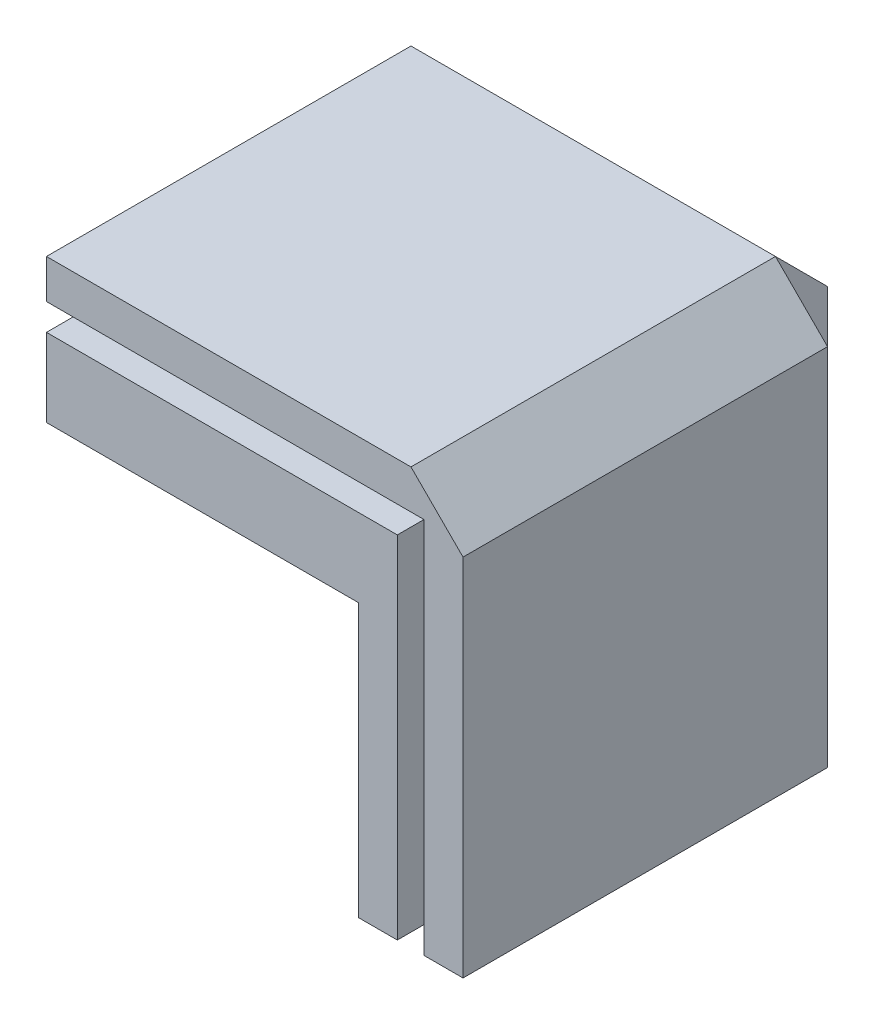
SolidWorks part; units mm, degrees
material "6061-T6 (SS)"
ref_plane "Front Plane" through (0, 0, 0) normal (0, 0, 1) x (1, 0, 0)
ref_plane "Top Plane" through (0, 0, 0) normal (0, 1, 0) x (1, 0, 0)
ref_plane "Right Plane" through (0, 0, 0) normal (1, 0, 0) x (0, 0, -1)
sketch "Sketch4" plane through (0, 0, 0) normal (0, 1, 0) x (1, 0, 0)
  line L1 (0, 0) -> (50.8, 0)
  line L2 (0, 0) -> (0, 50.8)
  line L3 (0, 50.8) -> (50.8, 50.8)
  line L4 (50.8, 0) -> (50.8, 50.8)
  dimension "D1" = 50.8
  dimension "D2" = 50.8
extrude "Boss-Extrude4" add sketch "Sketch4" along normal blind 50.8
sketch "Sketch5" plane through (0, 0, 0) normal (0, -1, 0) x (1, 0, 0)
  line L1 (0, 0) -> (38.0238, 0)
  line L2 (0, 0) -> (0, -38.0238)
  line L3 (0, -38.0238) -> (38.0238, -38.0238)
  line L4 (38.0238, 0) -> (38.0238, -38.0238)
  dimension "D1" = 38.0238
extrude "Cut-Extrude1" cut sketch "Sketch5" against normal blind 38.0238
sketch "Sketch6" plane through (0, 0, 0) normal (-1, 0, 0) x (0, 0, 1)
  line L7 (0, 50.8) -> (0, 38.0238) construction
  line L8 (-50.8, 0) -> (-38.0238, 0) construction
  line L9 (-46.0375, 0) -> (-42.7863, 0)
  line L10 (0, 46.0375) -> (0, 42.7863)
  line L13 (-46.0375, 4.7625) -> (-42.7863, 4.7625)
  line L14 (-42.7863, 4.7625) -> (-42.7863, 42.7863)
  line L15 (-42.7863, 42.7863) -> (-4.7625, 42.7863)
  line L16 (-4.7625, 42.7863) -> (-4.7625, 46.0375)
  line L17 (-4.7625, 46.0375) -> (-46.0375, 46.0375)
  line L18 (-46.0375, 46.0375) -> (-46.0375, 4.7625)
  line L20 (-42.7863, 0) -> (-42.7863, 42.7863)
  line L21 (-42.7863, 42.7863) -> (0, 42.7863)
  line L23 (0, 46.0375) -> (-46.0375, 46.0375)
  line L24 (-46.0375, 46.0375) -> (-46.0375, 0)
  dimension "D1" = 4.7625
extrude "Cut-Extrude2" cut sketch "Sketch6" against normal blind 31.6738
sketch "Sketch7" plane through (0, 0, 0) normal (0, 0, 1) x (1, 0, 0)
  line L0 (31.6738, 46.0375) -> (46.0375, 46.0375)
  line L1 (31.6738, 42.7863) -> (42.7863, 42.7863)
  line L2 (31.6738, 42.7863) -> (31.6738, 46.0375) construction
  line L3 (46.0375, 46.0375) -> (46.0375, 0)
  line L4 (42.7863, 42.7863) -> (42.7863, 0)
  line L5 (38.0238, 0) -> (50.8, 0) construction
  line L6 (42.7863, 0) -> (46.0375, 0)
  line L7 (50.8, 50.8) -> (50.8, 0) construction
  line L8 (38.0238, 38.0238) -> (38.0238, 0) construction
  line L9 (31.6738, 42.7863) -> (0, 42.7863) construction
  dimension "D1" = 4.7625
  dimension "D2" = 4.7625
extrude "Cut-Extrude3" cut sketch "Sketch7" against normal blind 31.6738 and the other way through all
sketch "Sketch8" plane through (0, 0, 0) normal (0, -1, 0) x (1, 0, 0)
  line L0 (31.6738, -46.0375) -> (46.0375, -46.0375)
  line L1 (46.0375, -31.6738) -> (46.0375, -46.0375)
  line L2 (42.7863, -31.6738) -> (42.7863, -42.7863)
  line L3 (31.6738, -42.7863) -> (42.7863, -42.7863)
  line L4 (31.6738, -46.0375) -> (31.6738, -42.7863) construction
  line L5 (31.6738, -42.7863) -> (0, -42.7863) construction
  line L6 (31.6738, -46.0375) -> (31.6738, -42.7863)
  line L7 (42.7863, -31.6738) -> (46.0375, -31.6738)
extrude "Cut-Extrude4" cut sketch "Sketch8" against normal blind 31.6738
chamfer "Chamfer1" distance 6.35 angle 45 3 edges at (50.8, 50.8, -25.4) (50.8, 25.4, -50.8) (25.4, 50.8, -50.8)
sketch "Sketch9" plane through (38.0238, 0, 0) normal (-1, 0, 0) x (0, 0, 1)
  line L0 (0, 38.0238) -> (0, 0) construction
  line L1 (-38.0238, 38.0238) -> (0, 38.0238)
  line L2 (-38.0238, 38.0238) -> (-38.0238, 33.2613)
  line L3 (-38.0238, 33.2613) -> (0, 33.2613)
  line L4 (0, 38.0238) -> (0, 33.2613)
  dimension "D1" = 4.7625
extrude "Boss-Extrude5" add sketch "Sketch9" along normal up to surface (38.0238 mm away) up to face at (0, 26.9367, -26.9367)
sketch "Sketch10" plane through (0, 0, 0) normal (-1, 0, 0) x (0, 0, 1)
  line L1 (-42.7863, 42.7863) -> (-17.0053, 42.7863)
  line L2 (-42.7863, 42.7863) -> (-42.7863, 39.5605)
  line L3 (-42.7863, 39.5605) -> (-17.0053, 39.5605)
  line L4 (-17.0053, 42.7863) -> (-17.0053, 39.5605)
  dimension "D1" = 25.781
  dimension "D2" = 3.2258
extrude "Cut-Extrude5" cut sketch "Sketch10" against normal up to surface (31.6738 mm away) up to face at (31.6738, 40.1659, -40.1659)
